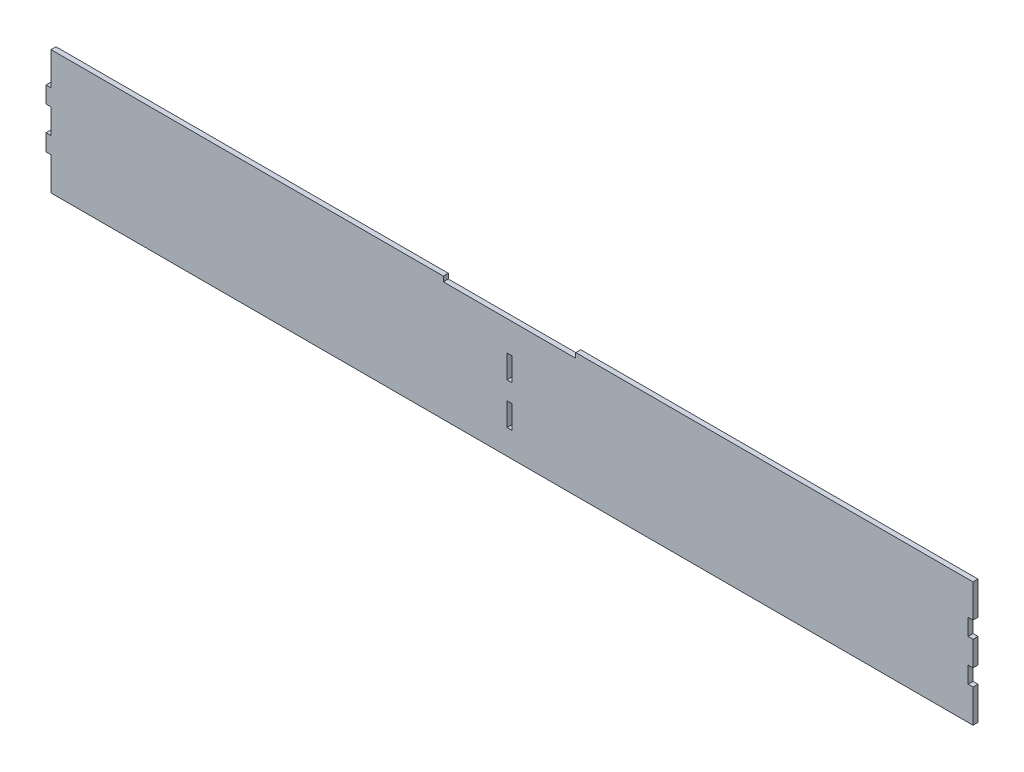
SolidWorks part; units mm, degrees
ref_plane "Front" through (0, 0, 0) normal (0, 0, 1) x (1, 0, 0)
ref_plane "Top" through (0, 0, 0) normal (0, 1, 0) x (1, 0, 0)
ref_plane "Right" through (0, 0, 0) normal (1, 0, 0) x (0, 0, -1)
sketch "Sketch1" plane through (0, 0, 0) normal (0, 0, 1) x (1, 0, 0)
  line L1 (-232.3449, 214.489) -> (327.6551, 214.489)
  line L2 (-232.3449, 214.489) -> (-232.3449, 139.489)
  line L3 (-232.3449, 139.489) -> (327.6551, 139.489)
  line L4 (327.6551, 214.489) -> (327.6551, 139.489)
  dimension "D1" = 560
  dimension "D2" = 75
extrude "Boss-Extrude1" add sketch "Sketch1" along normal blind 3 contours L2 L1 L4 L3
sketch "Sketch2" plane through (0, 0, 3) normal (0, 0, 1) x (1, 0, 0)
  line L0 (-232.3449, 214.489) -> (327.6551, 214.489) construction
  line L1 (7.6551, 214.489) -> (87.6551, 214.489)
  line L2 (7.6551, 214.489) -> (7.6551, 211.489)
  line L3 (7.6551, 211.489) -> (87.6551, 211.489)
  line L4 (87.6551, 214.489) -> (87.6551, 211.489)
  line L5 (-232.3449, 214.489) -> (-232.3449, 139.489) construction
  line L6 (327.6551, 214.489) -> (327.6551, 139.489) construction
  line L8 (327.6551, 194.489) -> (324.6551, 194.489)
  line L9 (327.6551, 194.489) -> (327.6551, 184.489)
  line L10 (327.6551, 184.489) -> (324.6551, 184.489)
  line L11 (324.6551, 194.489) -> (324.6551, 184.489)
  line L12 (327.6551, 159.489) -> (324.6551, 159.489)
  line L13 (327.6551, 159.489) -> (327.6551, 169.489)
  line L14 (327.6551, 169.489) -> (324.6551, 169.489)
  line L15 (324.6551, 159.489) -> (324.6551, 169.489)
  point P18 (326.1551, 169.489)
  dimension "D1" = 80
  dimension "D2" = 240
  dimension "D3" = 10
  dimension "D4" = 3
  dimension "D5" = 3
  dimension "D6" = 20
  dimension "D7" = 10
  dimension "D8" = 15
extrude "Cut-Extrude1" cut sketch "Sketch2" against normal blind 3 contours L9 L8 L11 L10 | L13 L12 L15 L14
sketch "Sketch3" plane through (0, 0, 3) normal (0, 0, 1) x (1, 0, 0)
  line L0 (-232.3449, 214.489) -> (-232.3449, 139.489) construction
  line L1 (-232.3449, 214.489) -> (-229.3449, 214.489)
  line L2 (-232.3449, 214.489) -> (-232.3449, 194.489)
  line L3 (-232.3449, 194.489) -> (-229.3449, 194.489)
  line L4 (-229.3449, 214.489) -> (-229.3449, 194.489)
  line L5 (-232.3449, 139.489) -> (-229.3449, 139.489)
  line L6 (-232.3449, 139.489) -> (-232.3449, 159.489)
  line L7 (-232.3449, 159.489) -> (-229.3449, 159.489)
  line L8 (-229.3449, 139.489) -> (-229.3449, 159.489)
  line L9 (-232.3449, 169.489) -> (-229.3449, 169.489)
  line L10 (-232.3449, 169.489) -> (-232.3449, 184.489)
  line L11 (-232.3449, 184.489) -> (-229.3449, 184.489)
  line L12 (-229.3449, 169.489) -> (-229.3449, 184.489)
  dimension "D1" = 20
  dimension "D2" = 3
  dimension "D3" = 3
  dimension "D4" = 15
  dimension "D5" = 10
  dimension "D6" = 3
  dimension "D7" = 20
extrude "Cut-Extrude2" cut sketch "Sketch3" against normal blind 3 contours L2 L1 L4 L3 | L10 L9 L12 L11 | L6 L5 L8 L7
sketch "Sketch4" plane through (0, 0, 3) normal (0, 0, 1) x (1, 0, 0)
  line L0 (-229.3449, 214.489) -> (327.6551, 214.489) construction
  line L1 (7.6551, 214.489) -> (87.6551, 214.489)
  line L2 (7.6551, 214.489) -> (7.6551, 211.489)
  line L3 (7.6551, 211.489) -> (87.6551, 211.489)
  line L4 (87.6551, 214.489) -> (87.6551, 211.489)
  line L5 (327.6551, 214.489) -> (327.6551, 194.489) construction
  point P6 (87.6551, 212.989)
  dimension "D1" = 3
  dimension "D2" = 80
  dimension "D3" = 240
extrude "Cut-Extrude3" cut sketch "Sketch4" against normal blind 3 contours L2 L1 L4 L3
sketch "Sketch5" plane through (0, 0, 3) normal (0, 0, 1) x (1, 0, 0)
  line L0 (-229.3449, 139.489) -> (327.6551, 139.489) construction
  line L1 (46.1551, 139.489) -> (49.1551, 139.489)
  line L2 (46.1551, 139.489) -> (46.1551, 154.489)
  line L3 (46.1551, 154.489) -> (49.1551, 154.489)
  line L4 (49.1551, 139.489) -> (49.1551, 154.489)
  line L5 (327.6551, 159.489) -> (327.6551, 139.489) construction
  line L7 (7.6551, 211.489) -> (87.6551, 211.489) construction
  line L8 (46.1551, 154.489) -> (49.1551, 154.489)
  line L9 (46.1551, 154.489) -> (46.1551, 168.489)
  line L10 (46.1551, 168.489) -> (49.1551, 168.489)
  line L11 (49.1551, 154.489) -> (49.1551, 168.489)
  line L12 (46.1551, 168.489) -> (49.1551, 168.489)
  line L13 (46.1551, 168.489) -> (46.1551, 179.489)
  line L14 (46.1551, 179.489) -> (49.1551, 179.489)
  line L15 (49.1551, 168.489) -> (49.1551, 179.489)
  line L16 (46.1551, 179.489) -> (49.1551, 179.489)
  line L17 (46.1551, 179.489) -> (46.1551, 193.489)
  line L18 (46.1551, 193.489) -> (49.1551, 193.489)
  line L19 (49.1551, 179.489) -> (49.1551, 193.489)
  line L20 (46.1551, 193.489) -> (49.1551, 193.489)
  line L21 (46.1551, 193.489) -> (46.1551, 211.489)
  line L22 (46.1551, 211.489) -> (49.1551, 211.489)
  line L23 (49.1551, 193.489) -> (49.1551, 211.489)
  dimension "D1" = 3
  dimension "D2" = 278.5
  dimension "D3" = 15
  dimension "D4" = 14
  dimension "D5" = 11
  dimension "D6" = 14
extrude "Cut-Extrude4" cut sketch "Sketch5" against normal blind 10 contours L14 L19 L18 L17 | L3 L11 L10 L9
